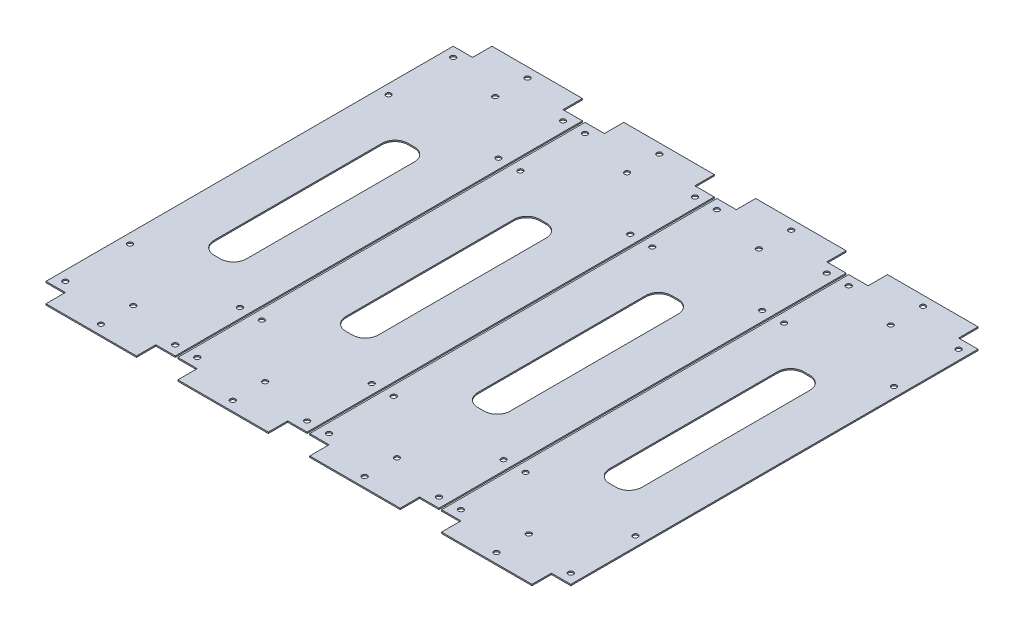
SolidWorks part; units mm, degrees
ref_plane "Front Plane" through (0, 0, 0) normal (0, 0, 1) x (1, 0, 0)
ref_plane "Top Plane" through (0, 0, 0) normal (0, 1, 0) x (1, 0, 0)
ref_plane "Right Plane" through (0, 0, 0) normal (1, 0, 0) x (0, 0, -1)
sketch "Sketch1" plane through (0, 0, 0) normal (0, 1, 0) x (1, 0, 0)
  line L0 (0, 140) -> (0, -140) construction
  line L1 (-35, 157.5) -> (35, 157.5) construction
  line L2 (-35, 157.5) -> (-35, -157.5) construction
  line L3 (-35, -157.5) -> (35, -157.5) construction
  line L4 (35, 157.5) -> (35, -157.5) construction
  line L5 (-35, 157.5) -> (35, -157.5) construction
  line L6 (-35, -157.5) -> (35, 157.5) construction
  line L7 (-35, 157.5) -> (-35, 172.5)
  line L8 (-12.5, 75) -> (12.5, 75)
  line L9 (-12.5, 75) -> (-12.5, -75)
  line L10 (-12.5, -75) -> (12.5, -75)
  line L11 (12.5, 75) -> (12.5, -75)
  line L12 (-12.5, 75) -> (12.5, -75) construction
  line L13 (-12.5, -75) -> (12.5, 75) construction
  line L14 (-35, 172.5) -> (35, 172.5)
  line L15 (35, 172.5) -> (35, 157.5)
  line L16 (35, 157.5) -> (50, 157.5)
  line L17 (50, 157.5) -> (50, -157.5)
  line L18 (50, -157.5) -> (35, -157.5)
  line L19 (35, -157.5) -> (35, -172.5)
  line L20 (35, -172.5) -> (-35, -172.5)
  line L21 (-35, -172.5) -> (-35, -157.5)
  line L22 (-35, -157.5) -> (-50, -157.5)
  line L23 (-50, -157.5) -> (-50, 157.5)
  line L24 (-50, 157.5) -> (-35, 157.5)
  line L25 (-42.5, 100) -> (42.5, 100) construction
  line L26 (-42.5, -150) -> (42.5, -150) construction
  line L27 (-42.5, -150) -> (-42.5, 150) construction
  line L28 (-42.5, 150) -> (42.5, 150) construction
  line L29 (42.5, -150) -> (42.5, 150) construction
  line L30 (-42.5, -150) -> (42.5, 150) construction
  line L31 (-42.5, 150) -> (42.5, -150) construction
  line L32 (-42.5, 150) -> (-42.5, 157.5) construction
  line L33 (-42.5, -100) -> (42.5, -100) construction
  line L34 (0, 157.5) -> (0, 172.5) construction
  line L35 (0, -157.5) -> (0, -172.5) construction
  circle A0 centre (0, 140) radius 2
  circle A1 centre (0, -140) radius 2
  circle A2 centre (42.5, 150) radius 2
  circle A3 centre (42.5, -150) radius 2
  circle A4 centre (42.5, -100) radius 2
  circle A5 centre (42.5, 100) radius 2
  circle A6 centre (-42.5, 150) radius 2
  circle A7 centre (-42.5, 100) radius 2
  circle A8 centre (-42.5, -100) radius 2
  circle A9 centre (-42.5, -150) radius 2
  circle A10 centre (0, 165) radius 2
  circle A11 centre (0, -165) radius 2
  point P0 (0, 0)
  point P10 (0, 0)
  point P23 (0, 0)
  dimension "D3" = 4
  dimension "D7" = 4
  dimension "D1" = 70
  dimension "D2" = 315
  dimension "D4" = 280
  dimension "D5" = 50
  dimension "D6" = 50
  dimension "D8" = 300
  dimension "D9" = 15
  dimension "D10" = 15
  dimension "D11" = 25
  dimension "D12" = 150
extrude "Boss-Extrude1" add sketch "Sketch1" along normal blind 1
fillet "Fillet1" radius 10 4 edges at (12.5, 0.5, 75) (-12.5, 0.5, 75) (12.5, 0.5, -75) (-12.5, 0.5, -75)
pattern_linear "LPattern1" count 4 spacing 102 along (1, 0, 0) of bodies 101
